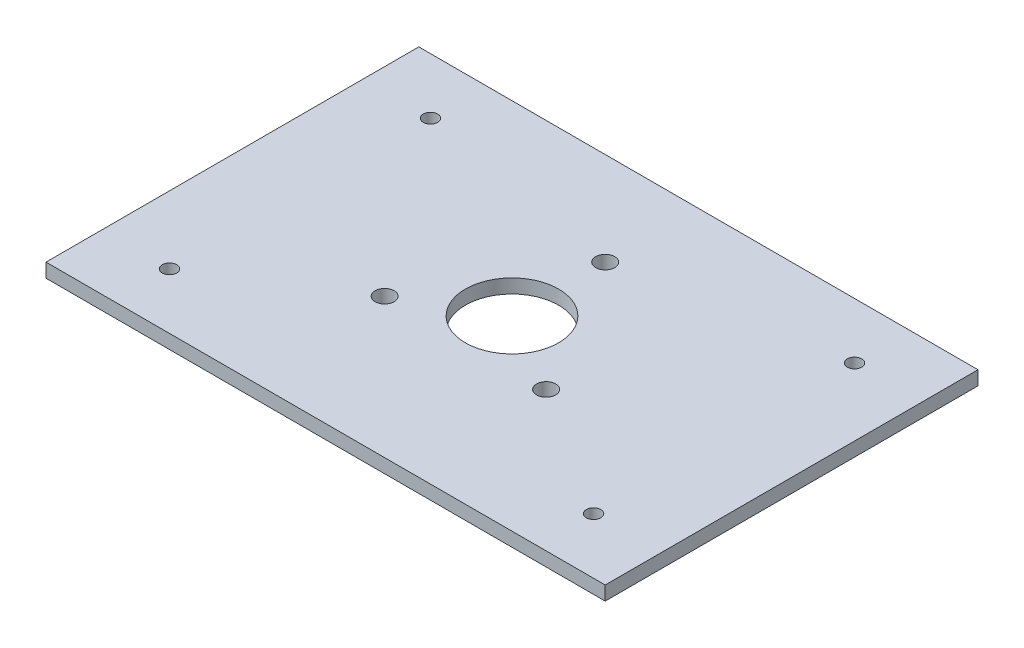
SolidWorks part; units mm, degrees
material "Thornel Mat VMA"
ref_plane "前视基准面" through (0, 0, 0) normal (0, 0, 1) x (1, 0, 0)
ref_plane "上视基准面" through (0, 0, 0) normal (0, 1, 0) x (1, 0, 0)
ref_plane "右视基准面" through (0, 0, 0) normal (1, 0, 0) x (0, 0, -1)
sketch "草图1" plane through (0, 0, 0) normal (0, 1, 0) x (1, 0, 0)
  line L0 (14.5, 80) -> (14.5, 0) construction
  line L1 (0, 0) -> (120, 0)
  line L2 (0, 0) -> (0, 80)
  line L3 (0, 80) -> (120, 80)
  line L4 (120, 0) -> (120, 80)
  line L5 (60, 80) -> (60, 0) construction
  line L6 (0, 40) -> (120, 40) construction
  circle A0 centre (60, 40) radius 20 construction
  circle A1 centre (60, 60) radius 2.05
  circle A4 centre (60, 40) radius 10
  circle A5 centre (77.3205, 30) radius 2.05
  circle A6 centre (42.6795, 30) radius 2.05
  circle A7 centre (14.5, 68) radius 1.55
  circle A8 centre (14.5, 12) radius 1.55
  circle A9 centre (105.5, 12) radius 1.55
  circle A10 centre (105.5, 68) radius 1.55
  point P15 (60, 60)
  point P17 (60, 40)
  point P280 (60, 40)
  dimension "D3" = 40
  dimension "D4" = 4.1
  dimension "D6" = 20
  dimension "D8" = 12
  dimension "D9" = 3.1
  dimension "D1" = 80
  dimension "D2" = 120
  dimension "D7" = 14.5
  dimension "D5" = 3
extrude "凸台-拉伸1" add sketch "草图1" along normal blind 3
